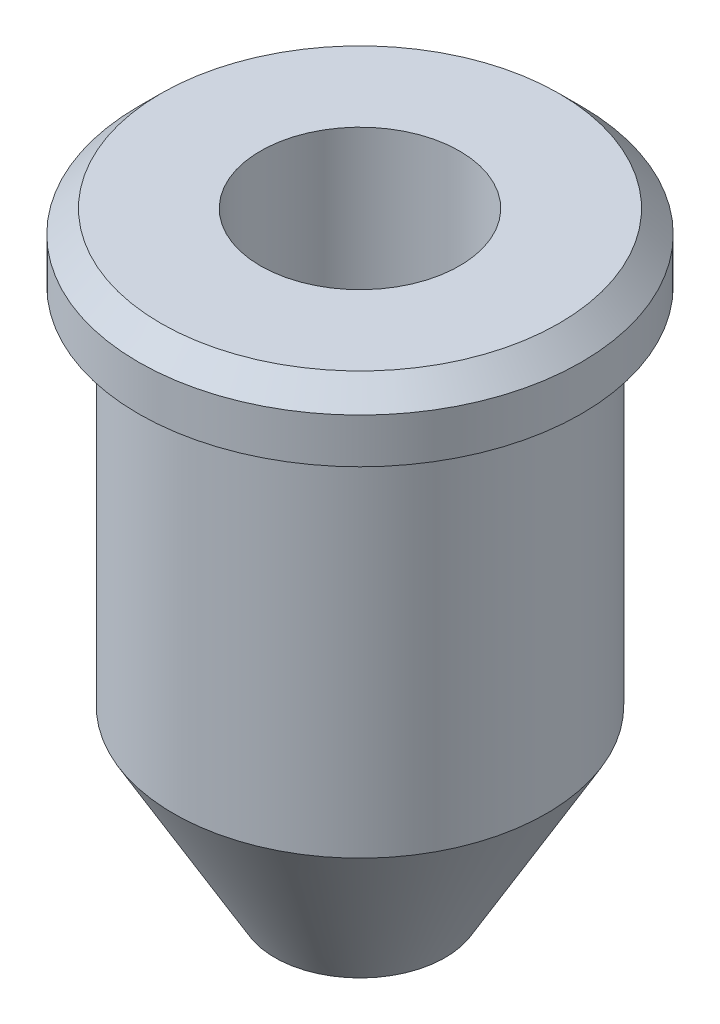
SolidWorks part; units mm, degrees
ref_plane "Front" through (0, 0, 0) normal (0, 0, 1) x (1, 0, 0)
ref_plane "Top" through (0, 0, 0) normal (0, 1, 0) x (1, 0, 0)
ref_plane "Right" through (0, 0, 0) normal (1, 0, 0) x (0, 0, -1)
sketch "Sketch1" plane through (0, 0, 0) normal (0, 0, 1) x (1, 0, 0)
  line L0 (0, 0) -> (0, 20.6375) construction
  line L1 (0, 5.969) -> (3.3893, 5.969)
  line L2 (0, 0) -> (2.9038, 0)
  line L3 (2.9038, 0) -> (6.35, 5.969)
  line L4 (6.35, 5.969) -> (6.35, 18.3515)
  line L5 (6.35, 18.3515) -> (7.5406, 18.3515)
  line L6 (7.5406, 18.3515) -> (7.5406, 19.8755)
  line L7 (6.7786, 20.6375) -> (7.5406, 19.8755)
  line L8 (3.3893, 5.969) -> (3.3893, 20.6375)
  line L9 (3.3893, 20.6375) -> (6.7786, 20.6375)
  line L10 (0, 5.969) -> (0, 0)
  line L11 (3.3893, 20.6375) -> (0, 20.6375) construction
  dimension "D2" = 12.3825
  dimension "D4" = 60
  dimension "D1" = 45
  dimension "D3" = 0.762
  dimension "D5" = 1.524
revolve "Revolve2" add sketch "Sketch1" angle 360 about L0
sketch "Sketch2" plane through (0, 0, 0) normal (0, 0, 1) x (1, 0, 0)
  line L0 (-6.35, 0) -> (6.35, 0) construction
  line L1 (-7.5406, 20.6375) -> (7.5406, 20.6375) construction
  line L2 (3.3893, 20.6375) -> (-3.3893, 20.6375) construction
  point P2 (0, 0)
  point P9 (0, 20.6375)
equation "\"D2@Sketch1\"=\"Height@Sketch1\"*.6"
